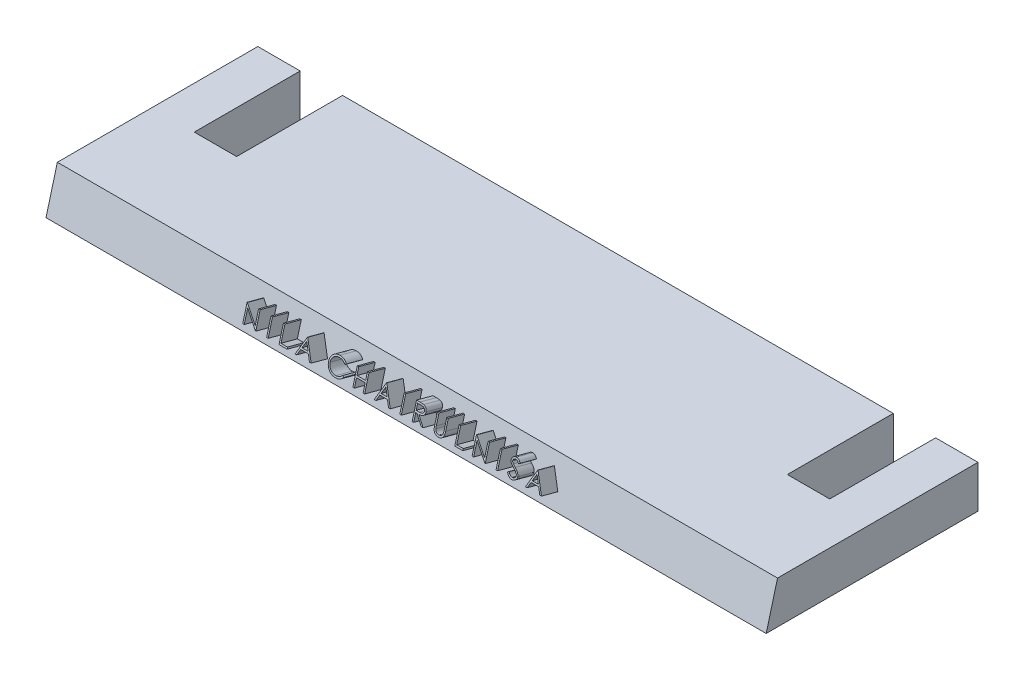
SolidWorks part; units mm, degrees
ref_plane "Front Plane" through (0, 0, 0) normal (0, 0, 1) x (1, 0, 0)
ref_plane "Top Plane" through (0, 0, 0) normal (0, 1, 0) x (1, 0, 0)
ref_plane "Right Plane" through (0, 0, 0) normal (1, 0, 0) x (0, 0, -1)
sketch "Sketch1" plane through (0, 0, 0) normal (0, 1, 0) x (1, 0, 0)
  line L0 (-75, 25) -> (-75, 0)
  line L1 (-85, -25) -> (85, -25)
  line L2 (-85, -25) -> (-85, 25)
  line L3 (-85, 25) -> (-75, 25)
  line L4 (85, -25) -> (85, 25)
  line L5 (-85, -25) -> (85, 25) construction
  line L6 (-85, 25) -> (85, -25) construction
  line L7 (-75, 0) -> (-65, 0)
  line L8 (-65, 0) -> (-65, 25)
  line L9 (0, 0) -> (0, 57.5201) construction
  line L10 (75, 25) -> (75, 0)
  line L11 (75, 0) -> (65, 0)
  line L12 (65, 0) -> (65, 25)
  line L13 (-65, 25) -> (65, 25)
  line L14 (75, 25) -> (85, 25)
  point P0 (0, 0)
  dimension "D1" = 170
  dimension "D2" = 50
  dimension "D3" = 10
  dimension "D4" = 10
  dimension "D5" = 25
extrude "Boss-Extrude1" add sketch "Sketch1" along normal blind 10
draft "Draft1" type of draft neutral plane draft angle 15 faces to draft 1 face at (0, 5, 25) neutral plane through (0, 0, 0) neutral plane normal (0, -1, 0) reverse direction yes parameters "D1"=15
sketch "Sketch2" plane through (0, 6.25, 23.3253) normal (0, 0.2588, 0.9659) x (1, 0, 0)
  text T0 "N I L A  C H A I R U L N I S A" font "Century Gothic" height 4
extrude "Boss-Extrude2" add sketch "Sketch2" along normal blind 4
